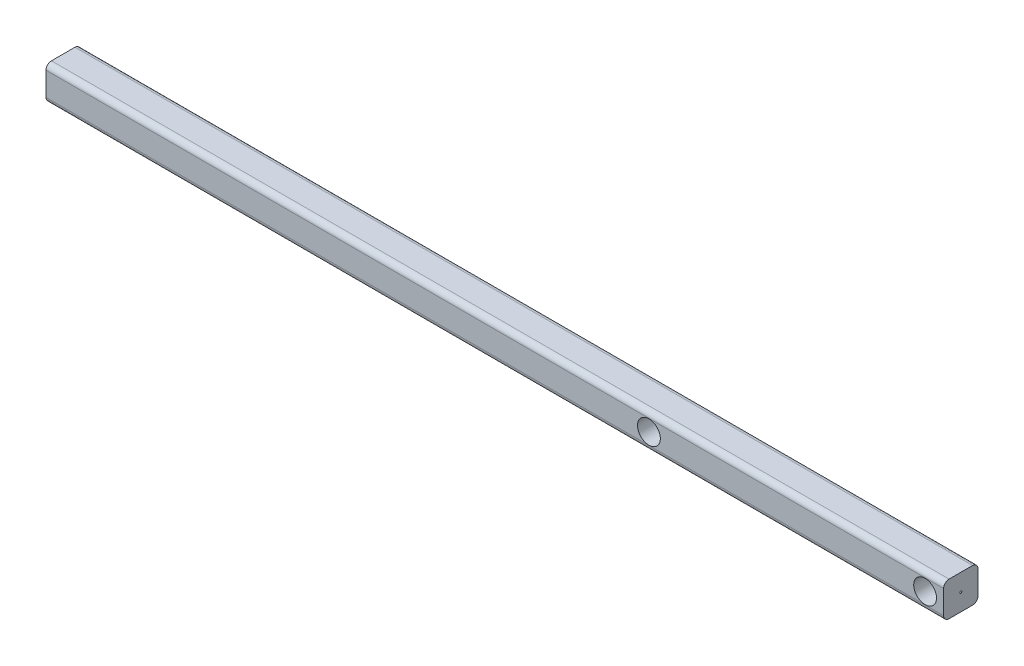
SolidWorks part; units mm, degrees
ref_plane "前视基准面" through (0, 0, 0) normal (0, 0, 1) x (1, 0, 0)
ref_plane "上视基准面" through (0, 0, 0) normal (0, 1, 0) x (1, 0, 0)
ref_plane "右视基准面" through (0, 0, 0) normal (1, 0, 0) x (0, 0, -1)
sketch "草图1" plane through (0, 0, 0) normal (1, 0, 0) x (0, 0, -1)
  line L1 (-3.16, -3.16) -> (3.16, -3.16)
  line L2 (-3.16, -3.16) -> (-3.16, 3.16)
  line L3 (-3.16, 3.16) -> (3.16, 3.16)
  line L4 (3.16, -3.16) -> (3.16, 3.16)
  line L5 (-3.16, -3.16) -> (3.16, 3.16) construction
  line L6 (-3.16, 3.16) -> (3.16, -3.16) construction
  circle A0 centre (0, 0) radius 0.1861
  point P0 (0, 0)
  dimension "D1" = 6.32
  dimension "D2" = 6.32
extrude "凸台-拉伸1" add sketch "草图1" along normal blind 165.1
fillet "圆角1" radius 1 4 edges at (82.55, -3.16, -3.16) (82.55, -3.16, 3.16) (82.55, 3.16, 3.16) (82.55, 3.16, -3.16)
sketch "草图2" plane through (0, 0, -3.16) normal (0, 0, -1) x (-1, 0, 0)
  circle A0 centre (-161.6921, -0.0182) radius 2.1
  circle A1 centre (-110.8921, -0.0182) radius 2.1
  dimension "D1" = 4.2
  dimension "D2" = 4.2
  dimension "D3" = 50.8
extrude "切除-拉伸1" cut sketch "草图2" against normal blind 165.1
